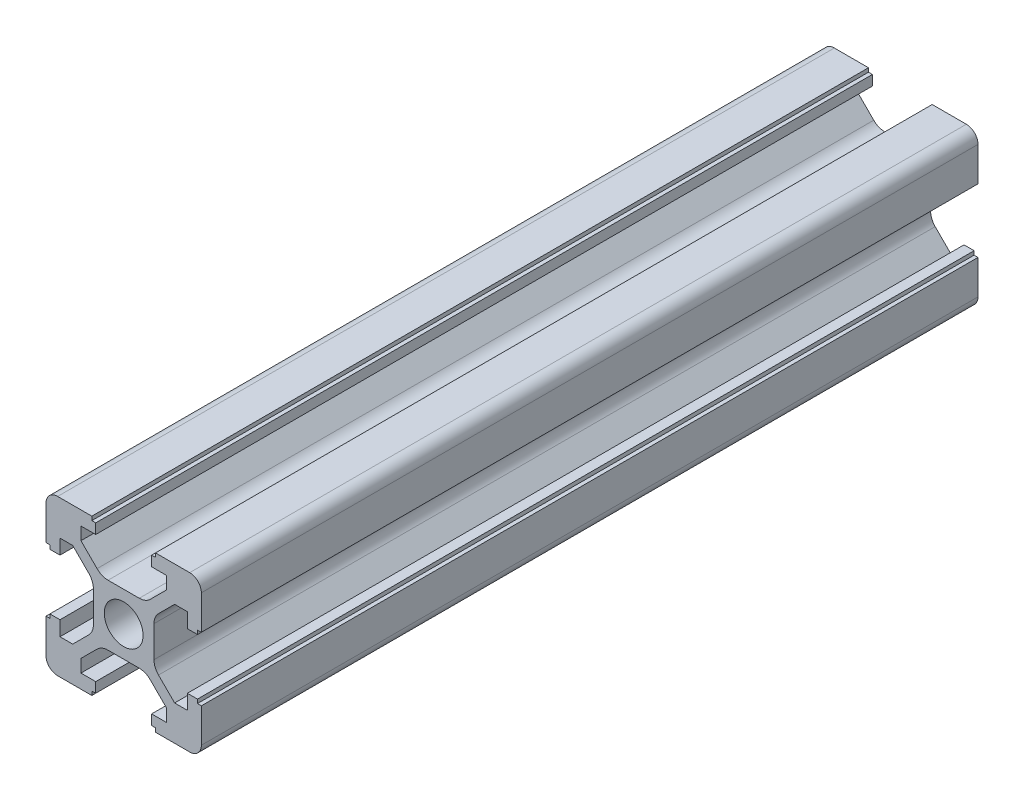
SolidWorks part; units mm, degrees
material "6063-O"
ref_plane "Front Plane" through (0, 0, 0) normal (0, 0, 1) x (1, 0, 0)
ref_plane "Top Plane" through (0, 0, 0) normal (0, 1, 0) x (1, 0, 0)
ref_plane "Right Plane" through (0, 0, 0) normal (1, 0, 0) x (0, 0, -1)
sketch "Sketch1" plane through (0, 0, 0) normal (0, 0, 1) x (1, 0, 0)
  line L0 (10, -4.1) -> (10, -8.5)
  line L1 (4.1, 10) -> (8.5, 10)
  line L2 (8.5, -10) -> (4.1, -10)
  line L3 (-8.5, -10) -> (-4.1, -10)
  line L4 (10, 8.5) -> (10, 4.1)
  line L7 (8.5, 10) -> (4.1, 10)
  line L8 (5.5, 6.5607) -> (3.4251, 4.4858)
  line L9 (8.5, 10) -> (4.1, 10)
  line L10 (3.9, 2.0109) -> (3.9, -2.0109)
  line L11 (2.0109, -3.9) -> (-2.0109, -3.9)
  line L12 (-3.9, -2.0109) -> (-3.9, 2.0109)
  line L13 (-2.0109, 3.9) -> (2.8393, 3.9)
  line L14 (2.5, 0) -> (22.2403, 0) construction
  line L15 (3.6, 9.5) -> (3.6, 8.2)
  line L16 (9.5, 3.6) -> (8.2, 3.6)
  line L17 (8.2, 3.6) -> (8.2, 5.5)
  line L18 (8.2, 5.5) -> (6.5607, 5.5)
  line L19 (10, -4.1) -> (10, -8.5)
  line L20 (4.1, 9.5) -> (3.6, 9.5)
  line L21 (4.1, 10) -> (4.1, 9.5)
  line L22 (8.5, 10) -> (4.1, 10)
  line L23 (10, 4.1) -> (9.5, 4.1)
  line L24 (9.5, 4.1) -> (9.5, 3.6)
  line L25 (5.5, 8.2) -> (5.5, 6.5607)
  line L26 (3.6, 8.2) -> (5.5, 8.2)
  line L27 (4.4858, 3.4251) -> (6.5607, 5.5)
  line L28 (10, -8.5) -> (10, -4.1)
  line L29 (6.5607, -5.5) -> (4.4858, -3.4251)
  line L30 (10, -8.5) -> (10, -4.1)
  line L31 (2.0109, -3.9) -> (-2.0109, -3.9)
  line L32 (3.9, 2.8393) -> (3.9, -2.0109)
  line L33 (9.5, -3.6) -> (8.2, -3.6)
  line L34 (3.6, -9.5) -> (3.6, -8.2)
  line L35 (3.6, -8.2) -> (5.5, -8.2)
  line L36 (5.5, -8.2) -> (5.5, -6.5607)
  line L37 (9.5, -4.1) -> (9.5, -3.6)
  line L38 (10, -4.1) -> (9.5, -4.1)
  line L39 (10, -8.5) -> (10, -4.1)
  line L40 (4.1, -10) -> (4.1, -9.5)
  line L41 (4.1, -9.5) -> (3.6, -9.5)
  line L42 (8.2, -5.5) -> (6.5607, -5.5)
  line L43 (8.2, -3.6) -> (8.2, -5.5)
  line L44 (3.4251, -4.4858) -> (5.5, -6.5607)
  line L45 (-4.1, -10) -> (-8.5, -10)
  line L46 (-10, -8.5) -> (-10, -4.1)
  line L47 (-8.5, -10) -> (-4.1, -10)
  line L48 (-5.5, -6.5607) -> (-3.4251, -4.4858)
  line L49 (-8.5, -10) -> (-4.1, -10)
  line L50 (-3.9, -2.0109) -> (-3.9, 2.0109)
  line L51 (2.0109, -3.9) -> (-2.0109, -3.9)
  line L52 (-3.6, -9.5) -> (-3.6, -8.2)
  line L53 (-9.5, -3.6) -> (-8.2, -3.6)
  line L54 (-8.2, -3.6) -> (-8.2, -5.5)
  line L55 (-8.2, -5.5) -> (-6.5607, -5.5)
  line L56 (-4.1, -9.5) -> (-3.6, -9.5)
  line L57 (-4.1, -10) -> (-4.1, -9.5)
  line L58 (-8.5, -10) -> (-4.1, -10)
  line L59 (-10, -4.1) -> (-9.5, -4.1)
  line L60 (-9.5, -4.1) -> (-9.5, -3.6)
  line L61 (-5.5, -8.2) -> (-5.5, -6.5607)
  line L62 (-3.6, -8.2) -> (-5.5, -8.2)
  line L63 (-4.4858, -3.4251) -> (-6.5607, -5.5)
  line L64 (-10, 4.1) -> (-10, 8.5)
  line L65 (-8.5, 10) -> (-4.1, 10)
  line L66 (-10, 8.5) -> (-10, 4.1)
  line L67 (-6.5607, 5.5) -> (-4.4858, 3.4251)
  line L68 (-10, 8.5) -> (-10, 4.1)
  line L69 (-2.0109, 3.9) -> (2.0109, 3.9)
  line L70 (-3.9, -2.0109) -> (-3.9, 2.0109)
  line L71 (-9.5, 3.6) -> (-8.2, 3.6)
  line L72 (-3.6, 9.5) -> (-3.6, 8.2)
  line L73 (-3.6, 8.2) -> (-5.5, 8.2)
  line L74 (-5.5, 8.2) -> (-5.5, 6.5607)
  line L75 (-9.5, 4.1) -> (-9.5, 3.6)
  line L76 (-10, 4.1) -> (-9.5, 4.1)
  line L77 (-10, 8.5) -> (-10, 4.1)
  line L78 (-4.1, 10) -> (-4.1, 9.5)
  line L79 (-4.1, 9.5) -> (-3.6, 9.5)
  line L80 (-8.2, 5.5) -> (-6.5607, 5.5)
  line L81 (-8.2, 3.6) -> (-8.2, 5.5)
  line L82 (-3.4251, 4.4858) -> (-5.5, 6.5607)
  line L83 (4.1, -10) -> (8.5, -10)
  arc A0 (2.0109, -3.9) -> (3.4251, -4.4858) centre (2.0109, -5.9) cw
  arc A1 (4.4858, -3.4251) -> (3.9, -2.0109) centre (5.9, -2.0109) cw
  arc A2 (3.9, 2.0109) -> (4.4858, 3.4251) centre (5.9, 2.0109) cw
  arc A3 (2.0109, 3.9) -> (3.4251, 4.4858) centre (2.0109, 5.9) ccw
  arc A4 (-2.0109, 3.9) -> (-3.4251, 4.4858) centre (-2.0109, 5.9) cw
  arc A5 (-4.4858, 3.4251) -> (-3.9, 2.0109) centre (-5.9, 2.0109) cw
  arc A6 (-3.4251, -4.4858) -> (-2.0109, -3.9) centre (-2.0109, -5.9) cw
  arc A7 (-3.9, -2.0109) -> (-4.4858, -3.4251) centre (-5.9, -2.0109) cw
  circle A8 centre (0, 0) radius 2.5
  arc A9 (-8.5, -10) -> (-10, -8.5) centre (-8.5, -8.5) cw
  arc A10 (-10, 8.5) -> (-8.5, 10) centre (-8.5, 8.5) cw
  arc A11 (8.5, 10) -> (10, 8.5) centre (8.5, 8.5) cw
  arc A12 (8.5, -10) -> (10, -8.5) centre (8.5, -8.5) ccw
  point P0 (0, 0)
  point P86 (0, 0)
  point P107 (10, -10)
  dimension "D3" = 2
  dimension "D5" = 5
  dimension "D2" = 1.5
  dimension "D8" = 1.5
  dimension "D6" = 4
  dimension "D7" = 6.1
  dimension "D11" = 0.5
  dimension "D12" = 0.5
extrude "Boss-Extrude2" add sketch "Sketch1" along normal blind 100
